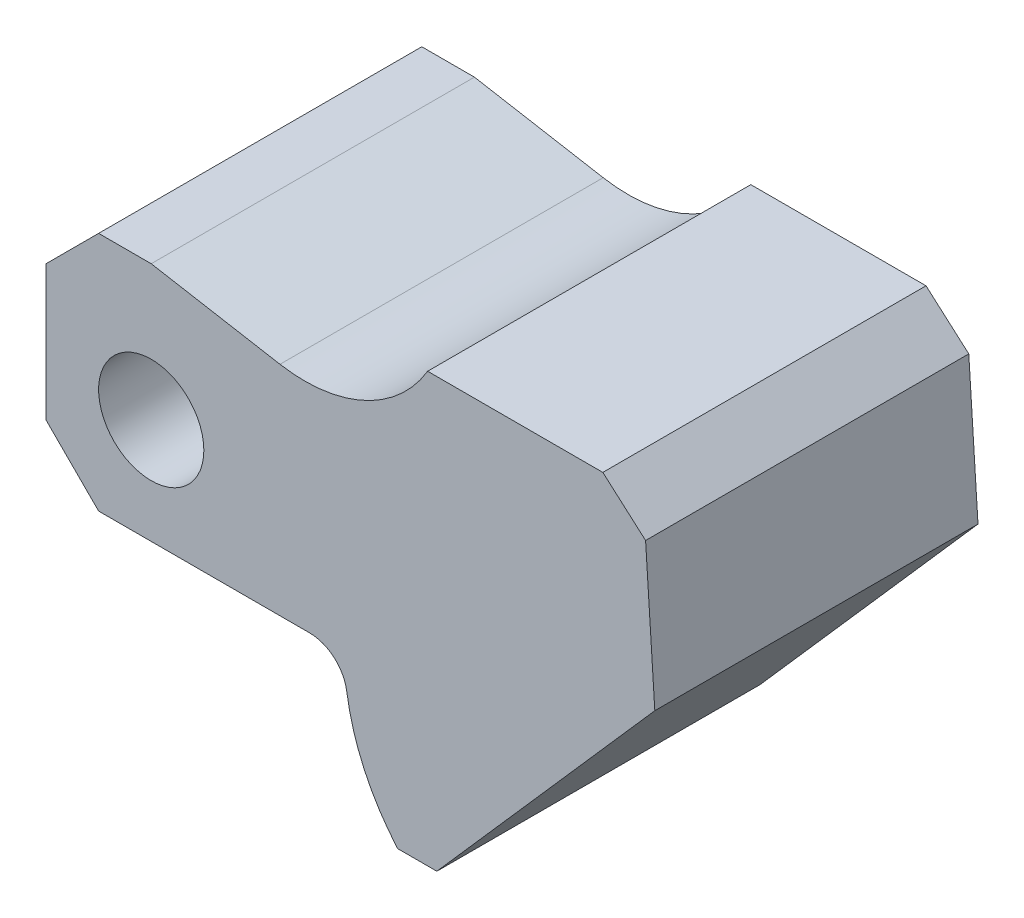
SolidWorks part; units mm, degrees
ref_plane "Front Plane" through (0, 0, 0) normal (0, 0, 1) x (1, 0, 0)
ref_plane "Top Plane" through (0, 0, 0) normal (0, 1, 0) x (1, 0, 0)
ref_plane "Right Plane" through (0, 0, 0) normal (1, 0, 0) x (0, 0, -1)
sketch "Sketch1" plane through (0, 0, 0) normal (0, 0, 1) x (1, 0, 0)
  line L0 (0, 0) -> (-7, 7)
  line L1 (-7, 7) -> (-7, 25)
  line L2 (-7, 25) -> (0, 32)
  line L3 (0, 32) -> (7, 32)
  line L4 (0, 0) -> (28.0666, 0)
  line L5 (39.7881, -19) -> (45, -19)
  line L6 (45, -19) -> (74, 14)
  line L7 (74, 14) -> (72.7742, 33)
  line L8 (72.7742, 33) -> (67.0845, 38)
  line L9 (67.0845, 38) -> (43.7742, 38)
  line L10 (7, 32) -> (24.1319, 28.9792)
  arc A0 (24.1319, 28.9792) -> (43.7742, 38) centre (27.4312, 47.6905) ccw
  circle A1 centre (7, 14) radius 7
  arc A2 (33.0123, -4.2647) -> (39.7881, -19) centre (61.697, 0) ccw
  arc A3 (33.0123, -4.2647) -> (28.0666, 0) centre (28.0666, -5) ccw
  point P9 (61.697, 0)
  dimension "D14" = 38
  dimension "D15" = 10
  dimension "D16" = 14
  dimension "D20" = 58
  dimension "D21" = 10
  dimension "D1" = 45
  dimension "D2" = 7
  dimension "D3" = 32
  dimension "D4" = 7
  dimension "D5" = 45
  dimension "D6" = 14
  dimension "D7" = 29
  dimension "D8" = 45
  dimension "D9" = 5
  dimension "D10" = 24
  dimension "D11" = 57
  dimension "D12" = 29
  dimension "D13" = 81
  dimension "D17" = 14
  dimension "D18" = 14
  dimension "D19" = 19
  dimension "D22" = 19
extrude "Boss-Extrude1" add sketch "Sketch1" along normal blind 43
